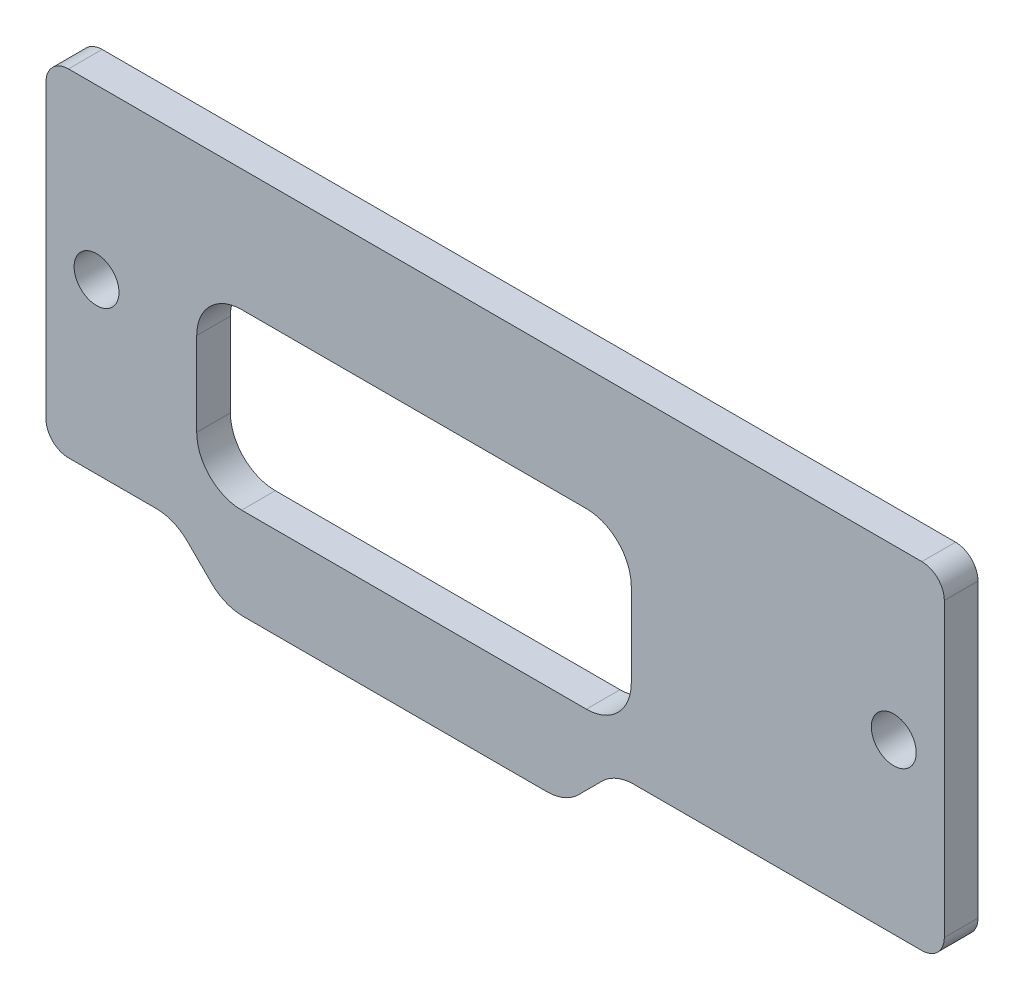
SolidWorks part; units mm, degrees
material "PA 类型 6"
ref_plane "前视基准面" through (0, 0, 0) normal (0, 0, 1) x (1, 0, 0)
ref_plane "上视基准面" through (0, 0, 0) normal (0, 1, 0) x (1, 0, 0)
ref_plane "右视基准面" through (0, 0, 0) normal (1, 0, 0) x (0, 0, -1)
sketch "草图1" plane through (0, 0, 0) normal (0, 0, 1) x (1, 0, 0)
  line L1 (-21.7384, 9.3368) -> (13.7616, 9.3368) construction
  line L2 (-21.7384, 9.3368) -> (-21.7384, -0.6632) construction
  line L3 (-21.7384, -0.6632) -> (13.7616, -0.6632) construction
  line L4 (13.7616, 9.3368) -> (13.7616, -0.6632) construction
  line L5 (-21.7384, 9.3368) -> (13.7616, -0.6632) construction
  line L6 (-21.7384, -0.6632) -> (13.7616, 9.3368) construction
  line L7 (-23.9884, 11.8368) -> (16.0116, 11.8368)
  line L8 (-23.9884, 11.8368) -> (-23.9884, -3.1632)
  line L9 (-23.9884, -3.1632) -> (16.0116, -3.1632)
  line L10 (16.0116, 11.8368) -> (16.0116, -3.1632)
  line L11 (-23.9884, 11.8368) -> (16.0116, -3.1632) construction
  line L12 (-23.9884, -3.1632) -> (16.0116, 11.8368) construction
  circle A0 centre (-21.7384, 9.3368) radius 1.1 construction
  circle A1 centre (-21.7384, -0.6632) radius 1.1 construction
  circle A2 centre (13.7616, -0.6632) radius 1.1 construction
  circle A3 centre (13.7616, 9.3368) radius 1.1 construction
  circle A4 centre (-21.7384, 4.3368) radius 1
  circle A5 centre (13.7616, 4.3368) radius 1
  point P0 (-3.9884, 4.3368)
  point P9 (-3.9884, 4.3368)
  dimension "D3" = 40
  dimension "D4" = 15
  dimension "D1" = 10
  dimension "D2" = 35.5
extrude "凸台-拉伸1" add sketch "草图1" along normal blind 1.5
sketch "草图2" plane through (0, 0, 1.5) normal (0, 0, 1) x (1, 0, 0)
  line L7 (-17.2774, 6.4097) -> (2.072, 6.4097)
  line L8 (-17.2774, 6.4097) -> (-17.2774, -1.3235)
  line L9 (-17.2774, -1.3235) -> (2.072, -1.3235)
  line L10 (2.072, 6.4097) -> (2.072, -1.3235)
  line L11 (-17.2774, 6.4097) -> (2.072, -1.3235) construction
  line L12 (-17.2774, -1.3235) -> (2.072, 6.4097) construction
  point P8 (-7.6027, 2.5431)
extrude "切除-拉伸1" cut sketch "草图2" against normal blind 1.5
fillet "圆角2" radius 1 4 edges at (16.0116, 11.8368, 0.75) (16.0116, -3.1632, 0.75) (-23.9884, -3.1632, 0.75) (-23.9884, 11.8368, 0.75)
fillet "圆角3" radius 2 4 edges at (2.072, 6.4097, 0.75) (2.072, -1.3235, 0.75) (-17.2774, -1.3235, 0.75) (-17.2774, 6.4097, 0.75)
sketch "草图3" plane through (0, 0, 1.5) normal (0, 0, 1) x (1, 0, 0)
  line L0 (-18.8396, -2.5877) -> (-16.0408, -5.3865)
  line L1 (-16.0408, -5.3865) -> (-0.8641, -5.3865)
  line L2 (-0.8641, -5.3865) -> (2.8881, -1.6343)
  line L3 (2.8881, -1.6343) -> (-18.8396, -2.5877)
  line L4 (-22.9884, -3.1632) -> (15.0116, -3.1632) construction
  dimension "D1" = 45
  dimension "D2" = 45
extrude "凸台-拉伸2" add sketch "草图3" against normal up to surface (1.5 mm away) up to face at (-7.6027, 2.5431, 0)
fillet "圆角4" radius 2 4 edges at (1.3592, -3.1632, 0.75) (-0.8641, -5.3865, 0.75) (-18.2641, -3.1632, 0.75) (-16.0408, -5.3865, 0.75)
